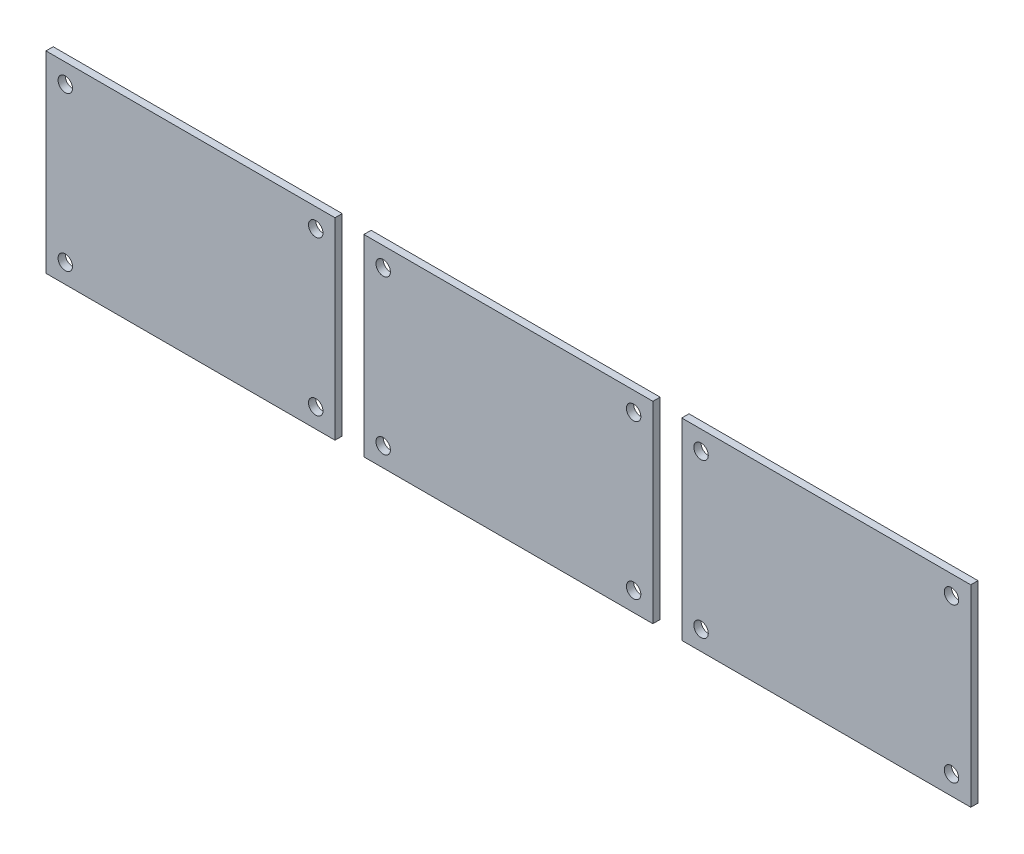
SolidWorks part; units mm, degrees
ref_plane "Спереди" through (0, 0, 0) normal (0, 0, 1) x (1, 0, 0)
ref_plane "Сверху" through (0, 0, 0) normal (0, 1, 0) x (1, 0, 0)
ref_plane "Справа" through (0, 0, 0) normal (1, 0, 0) x (0, 0, -1)
sketch "Эскиз1" plane through (0, 0, 0) normal (0, 0, 1) x (1, 0, 0)
  line L0 (66, 0) -> (126, 0)
  line L1 (0, 0) -> (60, 0)
  line L2 (0, 0) -> (0, 40)
  line L3 (0, 40) -> (60, 40)
  line L4 (60, 0) -> (60, 40)
  line L5 (66, 0) -> (66, 40)
  line L6 (66, 40) -> (126, 40)
  line L7 (126, 0) -> (126, 40)
  line L8 (132, 0) -> (192, 0)
  line L9 (132, 0) -> (132, 40)
  line L10 (132, 40) -> (192, 40)
  line L11 (192, 0) -> (192, 40)
  circle A0 centre (4, 4) radius 1.5
  circle A1 centre (56, 4) radius 1.5
  circle A2 centre (56, 36) radius 1.5
  circle A3 centre (4, 36) radius 1.5
  circle A4 centre (70, 36) radius 1.5
  circle A5 centre (122, 36) radius 1.5
  circle A6 centre (122, 4) radius 1.5
  circle A7 centre (70, 4) radius 1.5
  circle A8 centre (136, 36) radius 1.5
  circle A9 centre (188, 36) radius 1.5
  circle A10 centre (188, 4) radius 1.5
  circle A11 centre (136, 4) radius 1.5
  dimension "D6" = 3
  dimension "D1" = 60
  dimension "D2" = 40
  dimension "D4" = 4
  dimension "D5" = 4
  dimension "D3" = 3
  dimension "D7" = 2
  dimension "D8" = 2
  dimension "D9" = 3
extrude "Бобышка-Вытянуть1" add sketch "Эскиз1" along normal blind 1.5
